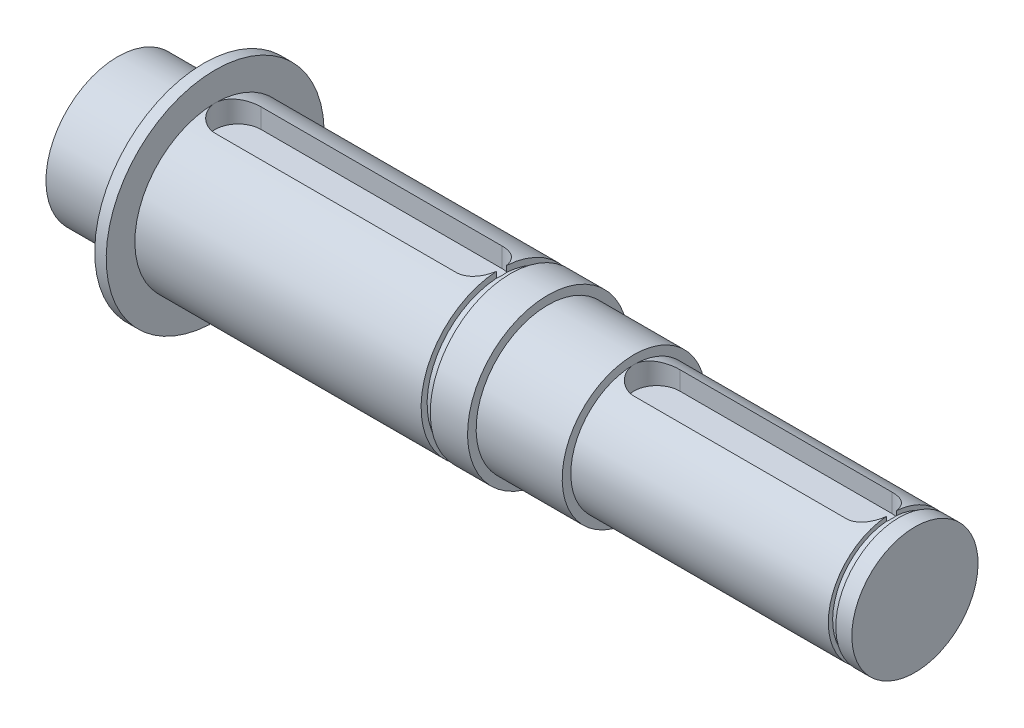
SolidWorks part; units mm, degrees
ref_plane "Спереди" through (0, 0, 0) normal (0, 0, 1) x (1, 0, 0)
ref_plane "Сверху" through (0, 0, 0) normal (0, 1, 0) x (1, 0, 0)
ref_plane "Справа" through (0, 0, 0) normal (1, 0, 0) x (0, 0, -1)
sketch "Эскиз1" plane through (0, 0, 0) normal (0, 0, 1) x (1, 0, 0)
  line L0 (0, 0) -> (0, 12.5)
  line L1 (0, 12.5) -> (15, 12.5)
  line L2 (15, 12.5) -> (15, 14)
  line L3 (15, 14) -> (15, 19)
  line L4 (15, 19) -> (17, 19)
  line L5 (17, 19) -> (17, 14)
  line L6 (17, 14) -> (75, 14)
  line L7 (75, 14) -> (75, 12.5)
  line L8 (75, 12.5) -> (90, 12.5)
  line L9 (90, 12.5) -> (90, 11)
  line L10 (90, 11) -> (139, 11)
  line L11 (139, 11) -> (139, 0)
  line L12 (139, 0) -> (0, 0) construction
  line L13 (0, 0) -> (139, 0)
  dimension "D1" = 25
  dimension "D2" = 28
  dimension "D3" = 22
  dimension "D4" = 25
  dimension "D5" = 15
  dimension "D6" = 60
  dimension "D8" = 139
  dimension "D9" = 15
revolve "Повернуть1" add sketch "Эскиз1" angle 360 about L12
sketch "Эскиз2" plane through (0, 0, 0) normal (0, 1, 0) x (1, 0, 0)
  line L2 (21, 0) -> (63, 0) construction
  line L4 (21, 4) -> (63, 4)
  line L5 (21, -4) -> (63, -4)
  arc A0 (21, 4) -> (21, -4) centre (21, 0) ccw
  arc A1 (63, -4) -> (63, 4) centre (63, 0) ccw
  point P8 (42, 0)
extrude "Вырез-Вытянуть1" cut sketch "Эскиз2" along normal through all from offset 10
sketch "Эскиз3" plane through (0, 0, 0) normal (0, 1, 0) x (1, 0, 0)
  line L2 (94, 0) -> (131, 0) construction
  line L4 (94, 4) -> (131, 4)
  line L5 (94, -4) -> (131, -4)
  arc A0 (94, 4) -> (94, -4) centre (94, 0) ccw
  arc A1 (131, -4) -> (131, 4) centre (131, 0) ccw
  point P8 (112.5, 0)
extrude "Вырез-Вытянуть2" cut sketch "Эскиз3" along normal through all from offset 7 contours L4 A1 L5 A0
sketch "Эскиз4" plane through (0, 0, 0) normal (1, 0, 0) x (0, 0, -1)
  circle A0 centre (0, 0) radius 14 construction
  circle A1 centre (0, 0) radius 14
  circle A2 centre (0, 0) radius 12.95
extrude "Вырез-Вытянуть3" cut sketch "Эскиз4" against normal blind 1.6 from offset 68.5
sketch "Эскиз5" plane through (0, 0, 0) normal (1, 0, 0) x (0, 0, -1)
  circle A0 centre (0, 0) radius 11 construction
  circle A1 centre (0, 0) radius 11
  circle A2 centre (0, 0) radius 10.25
extrude "Вырез-Вытянуть4" cut sketch "Эскиз5" against normal blind 1.3 from offset 136.2
